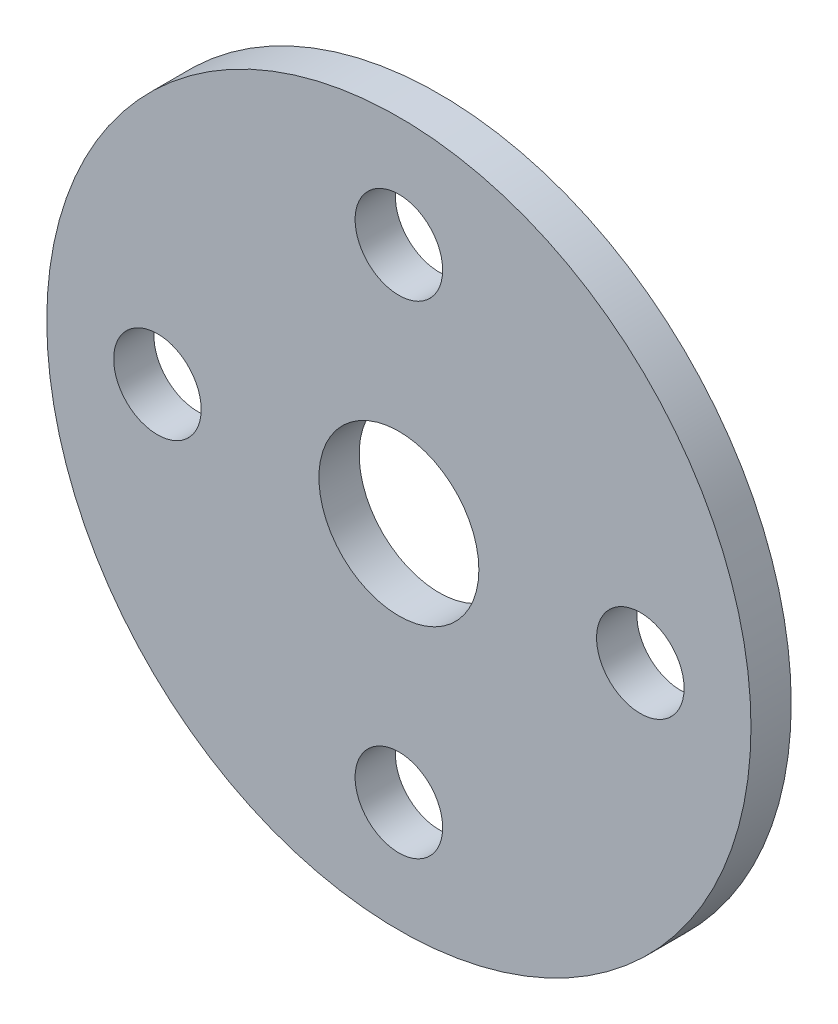
SolidWorks part; units mm, degrees
ref_plane "Front Plane" through (0, 0, 0) normal (0, 0, 1) x (1, 0, 0)
ref_plane "Top Plane" through (0, 0, 0) normal (0, 1, 0) x (1, 0, 0)
ref_plane "Right Plane" through (0, 0, 0) normal (1, 0, 0) x (0, 0, -1)
sketch "Sketch1" plane through (0, 0, 0) normal (0, 0, 1) x (1, 0, 0)
  circle A0 centre (0, 0) radius 17.5
  circle A2 centre (12, 0) radius 2.175
  circle A3 centre (0, 12) radius 2.175
  circle A4 centre (-12, 0) radius 2.175
  circle A5 centre (0, -12) radius 2.175
  circle A6 centre (0, 0) radius 3.975
  dimension "D1" = 4.35
  dimension "D2" = 4.35
  dimension "D3" = 4.35
  dimension "D4" = 4.35
  dimension "D5" = 7.95
extrude "Boss-Extrude1" add sketch "Sketch1" along normal blind 2
